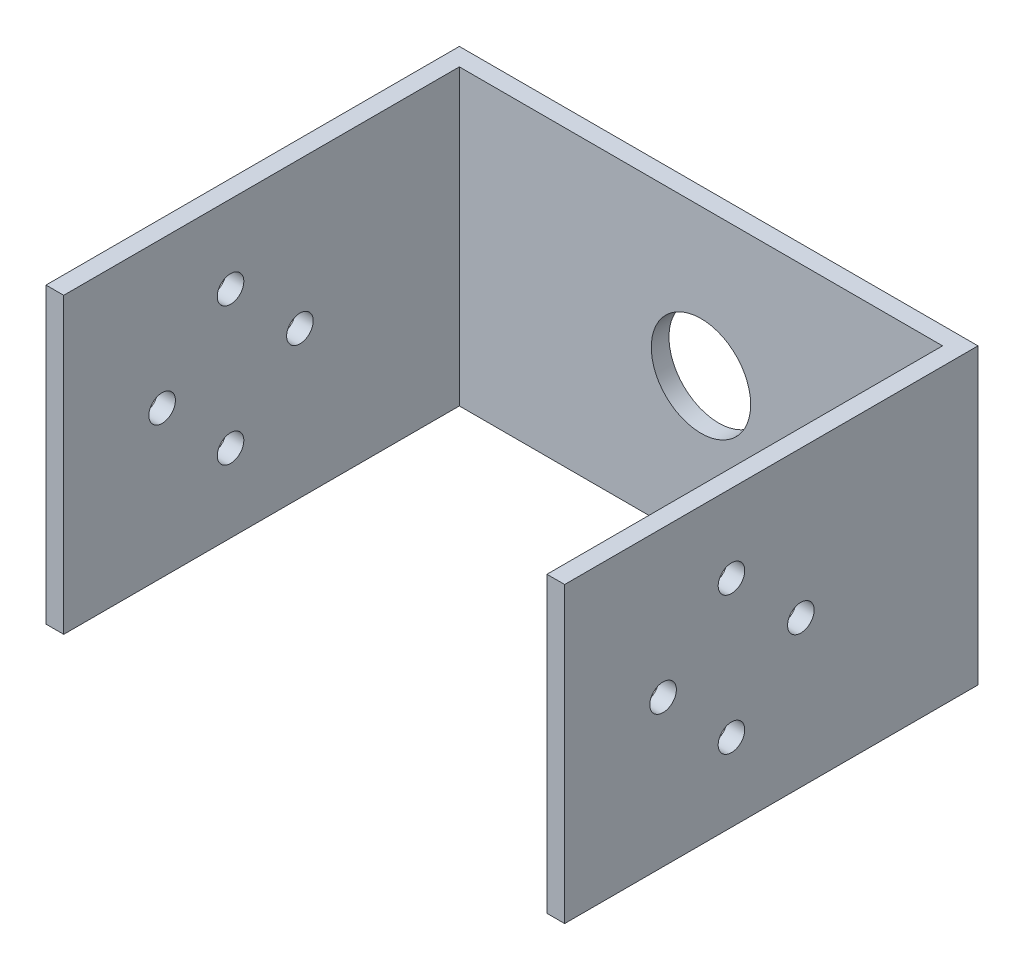
SolidWorks part; units mm, degrees
ref_plane "Plano frontal" through (0, 0, 0) normal (0, 0, 1) x (1, 0, 0)
ref_plane "Plano superior" through (0, 0, 0) normal (0, 1, 0) x (1, 0, 0)
ref_plane "Plano direito" through (0, 0, 0) normal (1, 0, 0) x (0, 0, -1)
sketch "Esboço1" plane through (0, 0, 0) normal (0, 0, 1) x (1, 0, 0)
  line L1 (-24.55, -14.92) -> (24.55, -14.92)
  line L2 (-24.55, -14.92) -> (-24.55, 14.92)
  line L3 (-24.55, 14.92) -> (24.55, 14.92)
  line L4 (24.55, -14.92) -> (24.55, 14.92)
  line L5 (-24.55, -14.92) -> (24.55, 14.92) construction
  line L6 (-24.55, 14.92) -> (24.55, -14.92) construction
  circle A0 centre (0, 0) radius 5.05
  point P0 (0, 0)
extrude "Ressalto-extrusão1" add sketch "Esboço1" along normal blind 1.8
ref_plane "Plano1" through (-24.55, 0, 0) normal (-1, 0, 0) x (0, 0, 1)
sketch "Esboço2" plane through (-24.55, 0, 0) normal (-1, 0, 0) x (0, 0, 1)
  line L0 (0, 14.92) -> (0, -14.92)
  line L1 (0, 14.92) -> (42, 14.92)
  line L2 (0, -14.92) -> (42, -14.92)
  line L3 (42, 14.92) -> (42, -14.92)
  line L4 (18, 0) -> (32, 0) construction
  circle A0 centre (32, 0) radius 1.35
  circle A2 centre (25.05, 7) radius 1.35
  circle A3 centre (18, 0) radius 1.35
  circle A4 centre (25.05, -7) radius 1.35
  dimension "D1" = 10
  dimension "D2" = 42
  dimension "D3" = 7
  dimension "D4" = 6.95
  dimension "D5" = 14
  dimension "D6" = 6.95
  dimension "D7" = 7
extrude "Ressalto-extrusão2" add sketch "Esboço2" along normal blind 1.8
ref_plane "Plano2" through (24.55, 0, 0) normal (1, 0, 0) x (0, 0, -1)
sketch "Esboço3" plane through (24.55, 0, 0) normal (1, 0, 0) x (0, 0, -1)
  line L0 (0, 14.92) -> (0, -14.92)
  line L1 (0, 14.92) -> (-42, 14.92)
  line L2 (0, -14.92) -> (-42, -14.92)
  line L3 (-42, 14.92) -> (-42, -14.92)
  circle A0 centre (-25.05, 7) radius 1.35
  circle A1 centre (-18, 0) radius 1.35
  circle A2 centre (-32, 0) radius 1.35
  circle A3 centre (-25.05, -7) radius 1.35
extrude "Ressalto-extrusão3" add sketch "Esboço3" along normal blind 1.8
